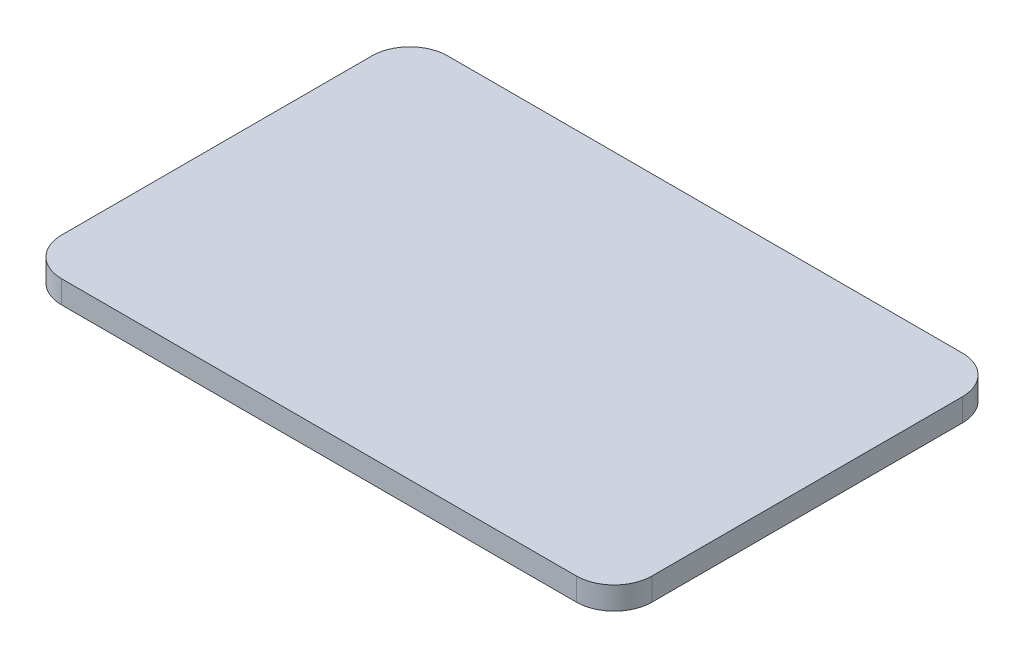
SolidWorks part; units mm, degrees
ref_plane "Front Plane" through (0, 0, 0) normal (0, 0, 1) x (1, 0, 0)
ref_plane "Top Plane" through (0, 0, 0) normal (0, 1, 0) x (1, 0, 0)
ref_plane "Right Plane" through (0, 0, 0) normal (1, 0, 0) x (0, 0, -1)
sketch "Sketch1" plane through (0, 0, 0) normal (0, 1, 0) x (1, 0, 0)
  line L1 (-39, 25.5) -> (39, 25.5)
  line L2 (-39, 25.5) -> (-39, -25.5)
  line L3 (-39, -25.5) -> (39, -25.5)
  line L4 (39, 25.5) -> (39, -25.5)
  line L5 (-39, 25.5) -> (39, -25.5) construction
  line L6 (-39, -25.5) -> (39, 25.5) construction
  point P0 (0, 0)
  dimension "D1" = 78
  dimension "D2" = 51
extrude "Boss-Extrude1" add sketch "Sketch1" along normal blind 3
fillet "Fillet1" radius 5 4 edges at (-39, 1.5, 25.5) (39, 1.5, 25.5) (39, 1.5, -25.5) (-39, 1.5, -25.5)
